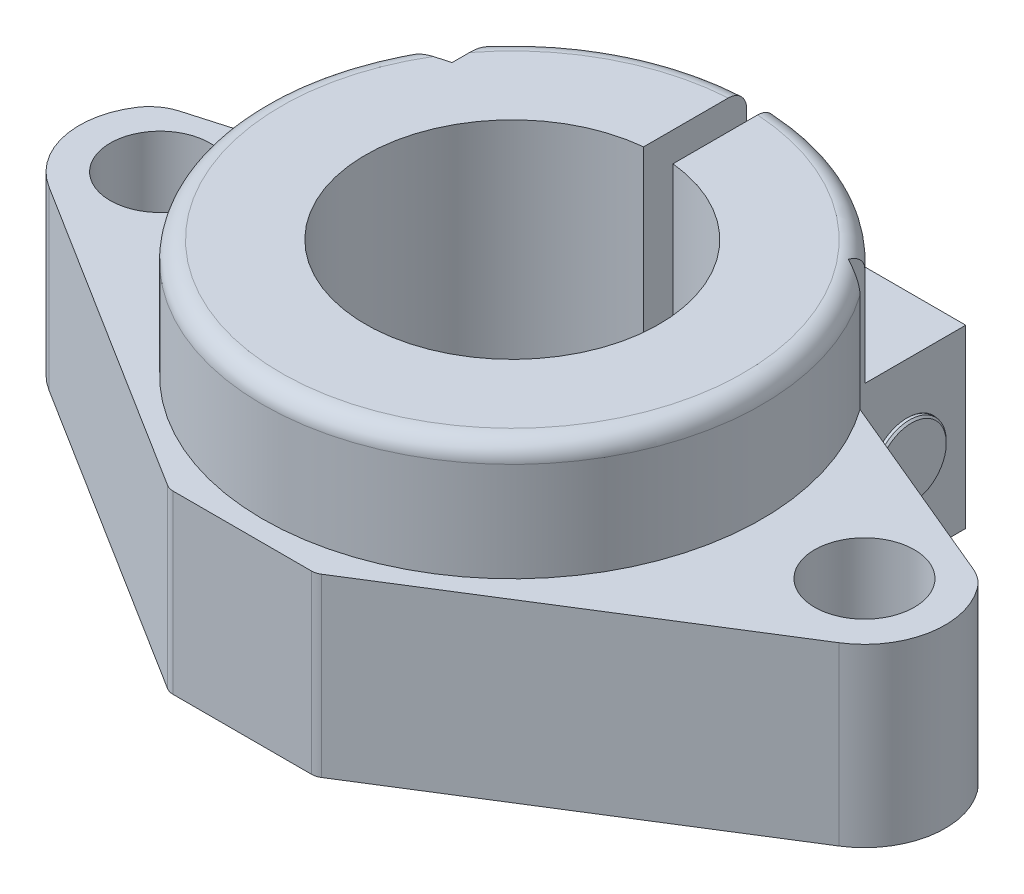
SolidWorks part; units mm, degrees
other "Markup1"
sketch "Sketch30" plane through (-28, 20, 19) normal (-0.8662, 0.4948, 0.0704) x (0.294, 0.3906, 0.8723)
ref_plane "Front Plane" through (0, 0, 0) normal (0, 0, 1) x (1, 0, 0)
ref_plane "Top Plane" through (0, 0, 0) normal (0, 1, 0) x (1, 0, 0)
ref_plane "Right Plane" through (0, 0, 0) normal (1, 0, 0) x (0, 0, -1)
sketch "Sketch1" plane through (0, 0, 0) normal (0, 1, 0) x (1, 0, 0)
  line L0 (0, 23.9567) -> (0, -22.6932) construction
  line L1 (-26.4411, 0) -> (25.427, 0) construction
  line L2 (5, -18.4) -> (-5, -18.4)
  line L3 (12.5, 18.4) -> (-12.5, 18.4)
  line L4 (-12.5, 18.4) -> (-27.7728, 4.002)
  line L5 (-5, -18.4) -> (-26.921, -4.6602)
  line L6 (5, -18.4) -> (26.921, -4.6602)
  line L7 (12.5, 18.4) -> (27.7728, 4.002)
  circle A1 centre (0, 0) radius 10 construction
  circle A2 centre (-24, 0) radius 3.4
  arc A3 (-27.7728, 4.002) -> (-26.921, -4.6602) centre (-24, 0) ccw
  circle A4 centre (24, 0) radius 3.4
  arc A5 (27.7728, 4.002) -> (26.921, -4.6602) centre (24, 0) cw
  point P20 (0, -18.4)
  point P21 (0, 18.4)
  dimension "D1" = 20
  dimension "D2" = 6.8
  dimension "D4" = 11
  dimension "D3" = 48
  dimension "D5" = 25
  dimension "D6" = 10
  dimension "D7" = 18.4
  dimension "D8" = 18.4
extrude "Boss-Extrude1" add sketch "Sketch1" along normal blind 12
sketch "Sketch3" plane through (0, 12, 0) normal (0, 1, 0) x (1, 0, 0)
  circle A0 centre (0, 0) radius 17
  dimension "D1" = 34
extrude "Boss-Extrude2" add sketch "Sketch3" along normal blind 8
fillet "Fillet1" radius 1.25 1 edges at (0, 20, 17)
sketch "Sketch2" plane through (0, 12, 0) normal (0, 1, 0) x (1, 0, 0)
  line L0 (12.5, 18.4) -> (12.5, 10.4)
  line L1 (12.5, 10.4) -> (27.7728, 4.002)
  line L2 (27.7728, 4.002) -> (12.5, 18.4)
  line L3 (-12.5, 18.4) -> (-12.5, 8.3996)
  line L4 (-12.5, 8.3996) -> (-27.7728, 4.002)
  line L5 (-27.7728, 4.002) -> (-12.5, 18.4)
  dimension "D1" = 8
  dimension "D2" = 10.0004
extrude "Cut-Extrude1" cut sketch "Sketch2" against normal through all both and the other way through all
sketch "Sketch4" plane through (0, 20, 0) normal (0, 1, 0) x (1, 0, 0)
  circle A0 centre (0, 0) radius 10
  dimension "D1" = 20
extrude "Cut-Extrude2" cut sketch "Sketch4" against normal through all both and the other way through all
sketch "Sketch5" plane through (0, 20, 0) normal (0, 1, 0) x (1, 0, 0)
  line L0 (0, 21.2575) -> (0, -21.4313) construction
  line L2 (1, 0) -> (-1, 0)
  line L3 (1, 0) -> (1, 20)
  line L4 (1, 20) -> (-1, 20)
  line L5 (-1, 0) -> (-1, 20)
  line L6 (1, 0) -> (-1, 20) construction
  line L7 (1, 20) -> (-1, 0) construction
  circle A0 centre (0, 0) radius 10 construction
  point P3 (0, 10)
  dimension "D1" = 2
  dimension "D2" = 20
extrude "Cut-Extrude3" cut sketch "Sketch5" against normal through all both
sketch "Sketch7" plane through (-12.5, 0, 0) normal (-1, 0, 0) x (0, 0, 1)
  line L0 (-8.3996, 0) -> (-18.4, 0) construction
  line L1 (-18.4, 12) -> (-18.4, 0) construction
  circle A0 centre (-14.4, 6) radius 3
  dimension "D1" = 6
  dimension "D2" = 6
  dimension "D3" = 4
extrude "Cut-Extrude4" cut sketch "Sketch7" against normal blind 12.5
fillet "Fillet2" radius 3 2 edges at (-27.7728, 6, -4.002) (27.7728, 6, -4.002)
fillet "Fillet3" radius 1 2 edges at (-5, 6, 18.4) (5, 6, 18.4)
hole_wizard "M5 Tapped Hole2" positions "Sketch15" profile "Sketch16" tap size "M5" standard "ISO" end condition through all
sketch "Sketch15" plane through (12.5, 0, 0) normal (1, 0, 0) x (0, 0, -1)
  line L0 (18.4, 12) -> (18.4, 0) construction
  line L1 (18.4, 0) -> (10.4, 0) construction
  point P0 (14.4, 6)
  dimension "D1" = 4
  dimension "D2" = 6
sketch "Sketch16" plane through (12.5, 6, -14.4) normal (0, 1, 0) x (0, 0, -1)
  line L0 (0, 0) -> (0, 42)
  line L1 (0, 42) -> (2.1, 42)
  line L2 (2.1, 42) -> (2.1, 0.425)
  line L3 (2.1, 0.425) -> (2.525, 0)
  line L5 (2.525, 0) -> (0, 0)
  line L6 (-2.1, 0.425) -> (-2.525, 0) construction
  line L11 (0, -6.35) -> (0, 107.95) construction
  dimension "Thru Tap Drill Dia." = 4.2
  dimension "Thru Tap Drill Depth" = 42
  dimension "Near C'Sink Dia." = 5.05
  dimension "Near C'Sink Angle" = 90
cosmetic thread "Hole Thread2" parameters "D2"=5
ref_plane "Plane3" through (-12.7, 0, 0) normal (-1, 0, 0) x (0, 0, 1)
sketch "Sketch26" plane through (-12.7, 0, 0) normal (-1, 0, 0) x (0, 0, 1)
  circle A0 centre (-14.4, 6) radius 2.5
  dimension "D1" = 5
extrude "Boss-Extrude4" add sketch "Sketch26" along normal blind 0.001 and the other way blind 25.5 separate body
sketch "Sketch28" plane through (-12.701, 0, 0) normal (-1, 0, 0) x (0, 0, 1)
  circle A0 centre (-14.4, 6) radius 4
  dimension "D1" = 8
extrude "Boss-Extrude5" add sketch "Sketch28" along normal blind 5
chamfer "Chamfer1" distance 0.125 angle 45 1 edges at (12.8, 6, -11.9)
sketch "Sketch29" plane through (-17.701, 0, 0) normal (-1, 0, 0) x (0, 0, 1)
  line L1 (-15.0678, 8.5705) -> (-16.96, 6.7069)
  line L2 (-16.96, 6.7069) -> (-16.2922, 4.1364)
  line L3 (-16.2922, 4.1364) -> (-13.7322, 3.4295)
  line L4 (-13.7322, 3.4295) -> (-11.84, 5.2931)
  line L5 (-11.84, 5.2931) -> (-12.5078, 7.8636)
  line L6 (-12.5078, 7.8636) -> (-15.0678, 8.5705)
  circle A0 centre (-14.4, 6) radius 2.3 construction
extrude "Cut-Extrude5" cut sketch "Sketch29" against normal blind 3
fillet "Fillet4" radius 0.75 1 edges at (-17.701, 6, -10.4)
